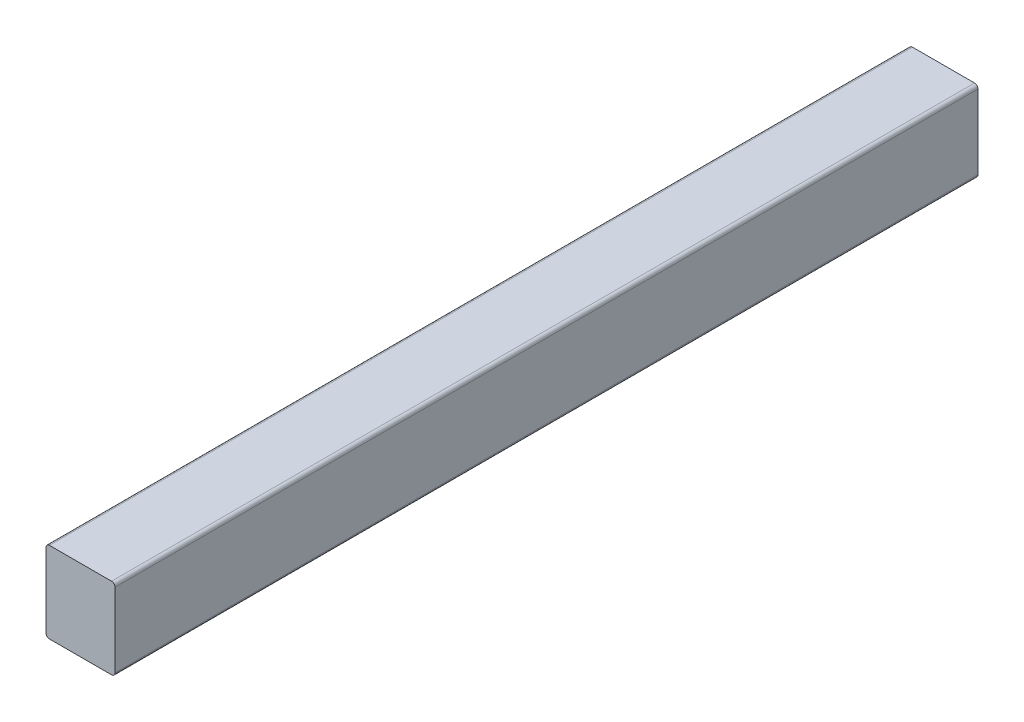
SolidWorks part; units mm, degrees
ref_plane "Front Plane" through (0, 0, 0) normal (0, 0, 1) x (1, 0, 0)
ref_plane "Top Plane" through (0, 0, 0) normal (0, 1, 0) x (1, 0, 0)
ref_plane "Right Plane" through (0, 0, 0) normal (1, 0, 0) x (0, 0, -1)
sketch "Sketch1" plane through (0, 0, 0) normal (0, 0, 1) x (1, 0, 0)
  line L1 (2, 2.35) -> (-2, 2.35)
  line L2 (2, 2.35) -> (2, -2.35)
  line L3 (2, -2.35) -> (-2, -2.35)
  line L4 (-2, 2.35) -> (-2, -2.35)
  line L5 (2, 2.35) -> (-2, -2.35) construction
  line L6 (2, -2.35) -> (-2, 2.35) construction
  point P0 (0, 0)
  dimension "D1" = 4
  dimension "D2" = 4.7
extrude "Boss-Extrude1" add sketch "Sketch1" along normal blind 50
fillet "Fillet1" radius 0.2 4 edges at (-2, -2.35, 25) (2, -2.35, 25) (-2, 2.35, 25) (2, 2.35, 25)
